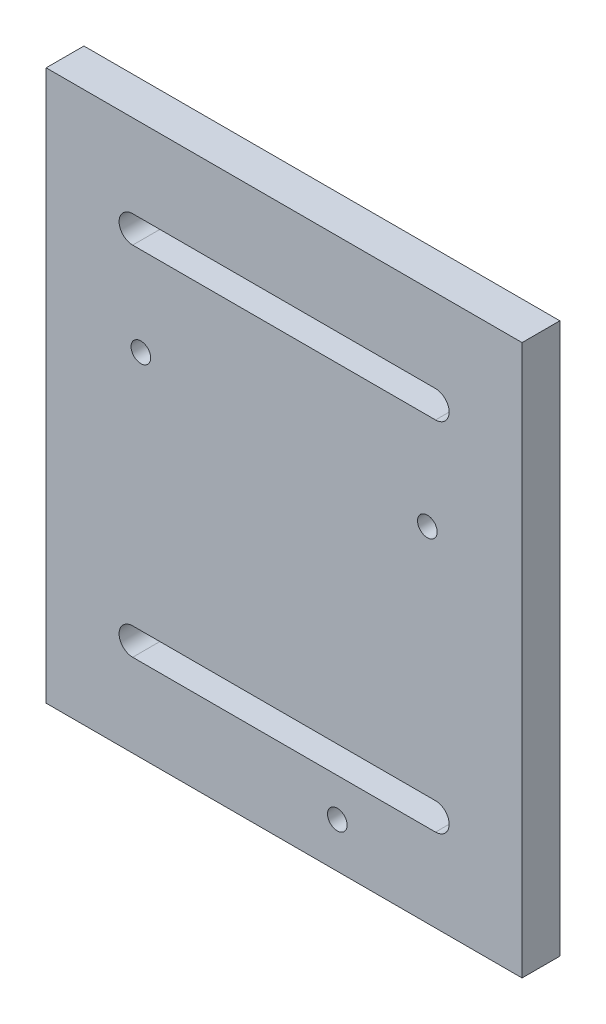
SolidWorks part; units mm, degrees
ref_plane "Front Plane" through (0, 0, 0) normal (0, 0, 1) x (1, 0, 0)
ref_plane "Top Plane" through (0, 0, 0) normal (0, 1, 0) x (1, 0, 0)
ref_plane "Right Plane" through (0, 0, 0) normal (1, 0, 0) x (0, 0, -1)
sketch "Sketch1" plane through (0, 0, 0) normal (0, 0, 1) x (1, 0, 0)
  line L0 (-25.4545, 30) -> (25.4545, 30) construction
  line L5 (-40, 46.25) -> (40, -46.25) construction
  line L6 (40, 46.25) -> (-40, -46.25) construction
  line L7 (-25.4545, 32.285) -> (25.4545, 32.285)
  line L8 (-25.4545, 27.715) -> (25.4545, 27.715)
  line L9 (-25.4545, -30) -> (25.4545, -30) construction
  line L10 (-25.4545, -27.715) -> (25.4545, -27.715)
  line L11 (-25.4545, -32.285) -> (25.4545, -32.285)
  line L12 (-40, 46.25) -> (40, 46.25)
  line L13 (40, -46.25) -> (40, 46.25)
  line L14 (-40, -46.25) -> (40, -46.25)
  line L15 (-40, -46.25) -> (-40, 46.25)
  arc A0 (-25.4545, 32.285) -> (-25.4545, 27.715) centre (-25.4545, 30) ccw
  arc A1 (25.4545, 27.715) -> (25.4545, 32.285) centre (25.4545, 30) ccw
  arc A2 (-25.4545, -27.715) -> (-25.4545, -32.285) centre (-25.4545, -30) ccw
  arc A3 (25.4545, -32.285) -> (25.4545, -27.715) centre (25.4545, -30) ccw
  circle A4 centre (-24.08, 12.8) radius 1.65
  circle A5 centre (24.08, 11.53) radius 1.65
  circle A6 centre (8.94, -38.71) radius 1.65
  point P0 (0, 0)
  point P8 (0, 30)
  point P13 (0, -30)
  dimension "D5" = 3.3
  dimension "D6" = 3.3
  dimension "D7" = 3.3
  dimension "D8" = 16.25
  dimension "D9" = 7.54
  dimension "D10" = 31.06
  dimension "D11" = 15.92
  dimension "D12" = 34.72
  dimension "D13" = 15.92
  dimension "D14" = 33.45
  dimension "D1" = 4.57
  dimension "D2" = 60
  dimension "D15" = 92.5
  dimension "D16" = 80
extrude "Boss-Extrude2" add sketch "Sketch1" along normal blind 6.35
